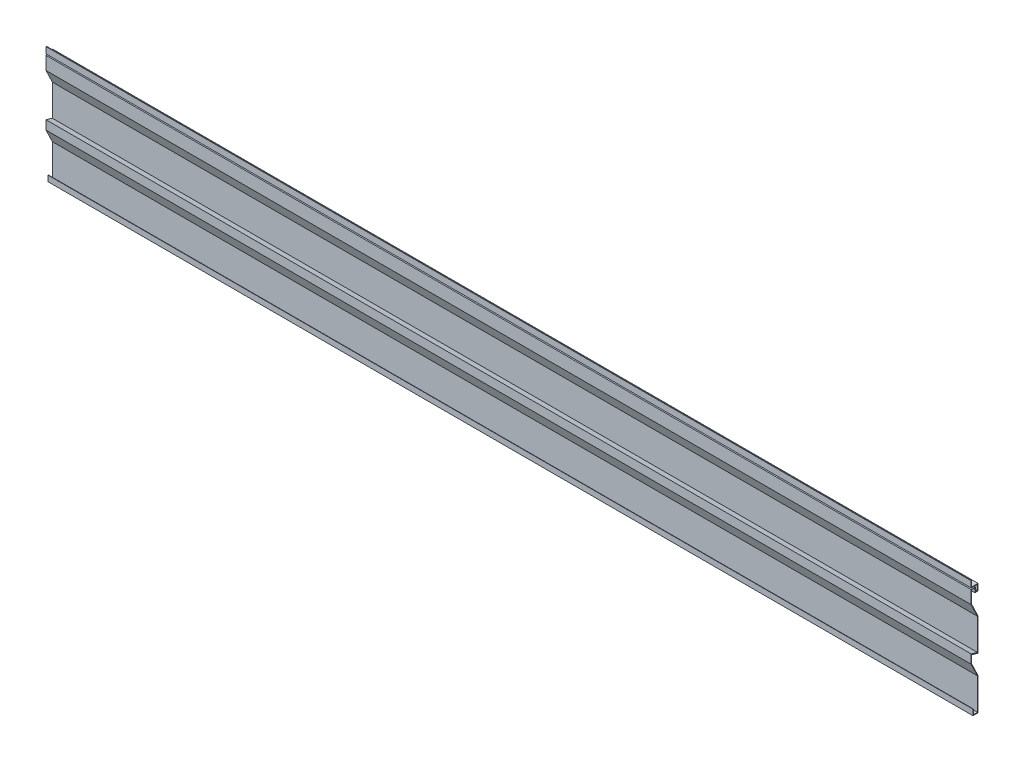
SolidWorks part; units mm, degrees
ref_plane "Спереди" through (0, 0, 0) normal (0, 0, 1) x (1, 0, 0)
ref_plane "Сверху" through (0, 0, 0) normal (0, 1, 0) x (1, 0, 0)
ref_plane "Справа" through (0, 0, 0) normal (1, 0, 0) x (0, 0, -1)
sketch "Эскиз1" plane through (0, 0, 0) normal (1, 0, 0) x (0, 0, -1)
  line L7 (-21.0405, -176.7428) -> (-11.0405, -176.7428)
  line L8 (-11.0405, -176.7428) -> (-11.0405, -112.7428)
  line L9 (-11.0405, -112.7428) -> (-23.4474, -86.7469)
  line L10 (-23.4474, -86.7469) -> (-23.4474, -71.1496)
  line L11 (-23.4474, -71.1496) -> (-11.0405, -74.6944)
  line L12 (-11.0405, -74.6944) -> (-11.0405, -10.6944)
  line L13 (-11.0405, -10.6944) -> (-23.4474, 15.3014)
  line L14 (-23.4474, 15.3014) -> (-23.4474, 40.3056)
  line L15 (-23.4474, 40.3056) -> (-17.2439, 40.3056)
  line L16 (-17.2439, 40.3056) -> (-17.2439, 32.0052)
  line L17 (-17.2439, 32.0052) -> (-11.0405, 32.0052)
  line L18 (-11.0405, 32.0052) -> (-11.0405, 45.1211)
  line L19 (-11.0405, 45.1211) -> (-23.4474, 45.1211)
  line L20 (-23.4474, 45.1211) -> (-23.4474, 56.3056)
  line L21 (-21.0405, -176.7428) -> (-21.0405, -165.4423)
  line L22 (-21.0405, -165.4423) -> (-20.3457, -165.4423)
  line L23 (-20.3457, -165.4423) -> (-20.3457, -175.264)
  line L24 (-20.3457, -175.264) -> (-12.1002, -175.264)
  line L25 (-12.1002, -175.264) -> (-12.1002, -112.7428)
  line L26 (-12.1002, -112.7428) -> (-24.5071, -86.7469)
  line L27 (-24.5071, -86.7469) -> (-24.5071, -69.0759)
  line L28 (-24.5071, -69.0759) -> (-12.1002, -72.6207)
  line L29 (-12.1002, -72.6207) -> (-12.1002, -10.6944)
  line L30 (-12.1002, -10.6944) -> (-24.5071, 15.3014)
  line L31 (-24.5071, 15.3014) -> (-24.5071, 41.2326)
  line L32 (-24.5071, 41.2326) -> (-16.2229, 41.2326)
  line L33 (-16.2229, 41.2326) -> (-16.2229, 33.3611)
  line L34 (-16.2229, 33.3611) -> (-12.1002, 33.3611)
  line L35 (-12.1002, 33.3611) -> (-12.1002, 43.8204)
  line L36 (-12.1002, 43.8204) -> (-24.5071, 43.8204)
  line L37 (-24.5071, 43.8204) -> (-24.5071, 56.3056)
  line L38 (-24.5071, 56.3056) -> (-23.4474, 56.3056)
extrude "Бобышка-Вытянуть1" add sketch "Эскиз1" along normal blind 1830
